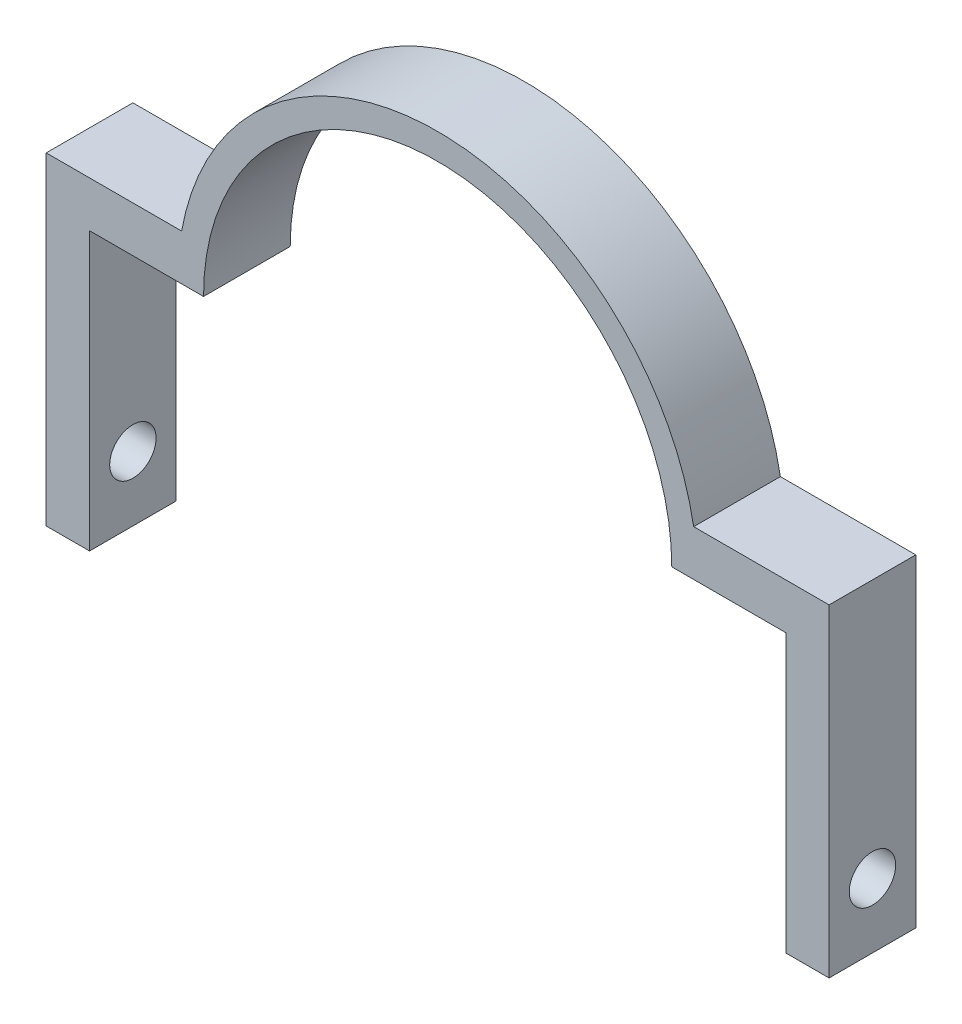
SolidWorks part; units mm, degrees
ref_plane "Front Plane" through (0, 0, 0) normal (0, 0, 1) x (1, 0, 0)
ref_plane "Top Plane" through (0, 0, 0) normal (0, 1, 0) x (1, 0, 0)
ref_plane "Right Plane" through (0, 0, 0) normal (1, 0, 0) x (0, 0, -1)
sketch "Sketch1" plane through (0, 0, 0) normal (0, 0, 1) x (1, 0, 0)
  line L3 (-17.15, 0) -> (-25.499, 0)
  line L4 (17.15, 0) -> (25.499, 0)
  line L5 (25.499, 0) -> (25.499, -20.32)
  line L6 (25.499, -20.32) -> (28.674, -20.32)
  line L7 (28.674, -20.32) -> (28.674, 3.3501)
  line L8 (28.674, 3.3501) -> (18.7531, 3.3501)
  line L9 (-28.674, 3.3501) -> (-18.7531, 3.3501)
  line L13 (-25.499, 0) -> (-25.499, -20.32)
  line L14 (-25.499, -20.32) -> (-28.674, -20.32)
  line L15 (-28.674, -20.32) -> (-28.674, 3.3501)
  arc A0 (17.15, 0) -> (-17.15, 0) centre (0, 0) ccw
  arc A1 (18.7531, 3.3501) -> (-18.7531, 3.3501) centre (0, 0) ccw
  dimension "D1" = 34.3
  dimension "D2" = 38.1
  dimension "D3" = 8.349
  dimension "D4" = 3.175
  dimension "D5" = 8.349
  dimension "D6" = 20.32
  dimension "D7" = 23.6701
  dimension "D8" = 20.32
  dimension "D9" = 23.6701
  dimension "D10" = 3.175
extrude "Boss-Extrude1" add sketch "Sketch1" along normal blind 6.35
sketch "Sketch2" plane through (28.674, 0, 0) normal (1, 0, 0) x (0, 0, -1)
  line L0 (-6.35, -20.32) -> (0, -20.32) construction
  line L2 (-6.35, 3.3501) -> (0, 3.3501) construction
  circle A0 centre (-3.175, -15.5878) radius 1.7
  point P4 (-3.175, -20.32)
  point P9 (-3.175, 3.3501)
  dimension "D1" = 3.4
  dimension "D3" = 18.938
  dimension "D2" = 0
extrude "Cut-Extrude1" cut sketch "Sketch2" against normal through all
